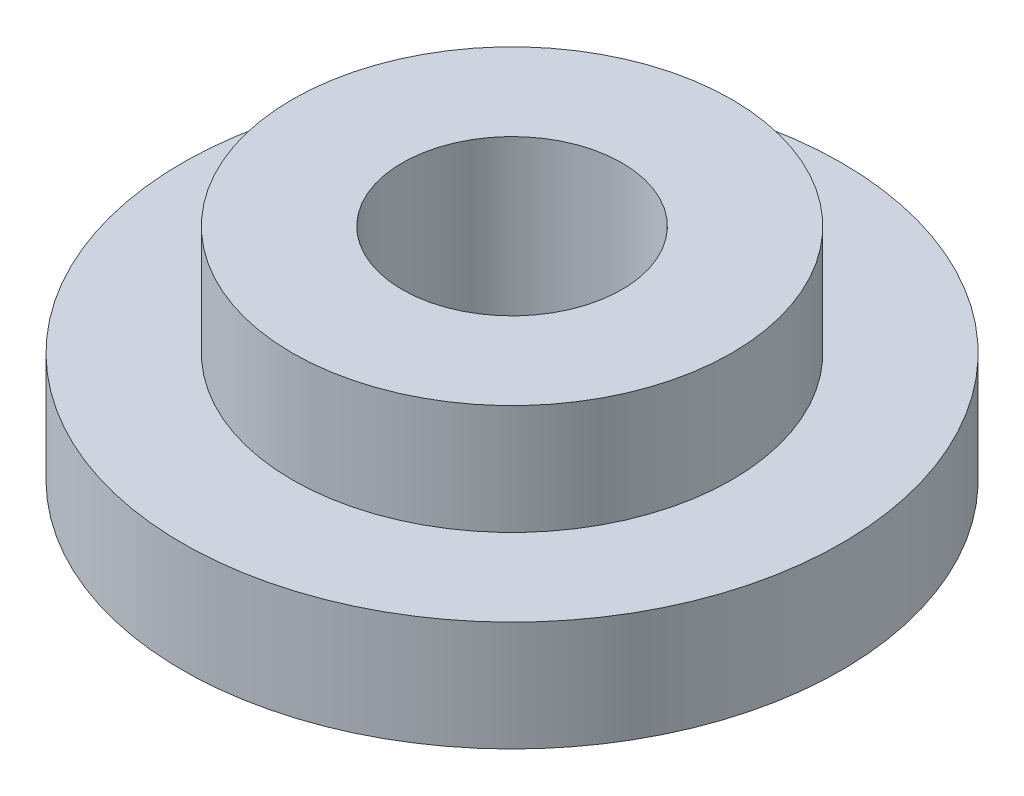
SolidWorks part; units mm, degrees
material "acero"
ref_plane "Alzado" through (0, 0, 0) normal (0, 0, 1) x (1, 0, 0)
ref_plane "Planta" through (0, 0, 0) normal (0, 1, 0) x (1, 0, 0)
ref_plane "Vista lateral" through (0, 0, 0) normal (1, 0, 0) x (0, 0, -1)
sketch "Croquis1" plane through (0, 0, 0) normal (0, 0, 1) x (1, 0, 0)
  line L0 (0, 0) -> (0, 4) construction
  line L1 (-2, 4) -> (-2, 0)
  line L2 (-2, 0) -> (-6, 0)
  line L3 (-6, 0) -> (-6, 2)
  line L4 (-6, 2) -> (-4, 2)
  line L5 (-4, 2) -> (-4, 4)
  line L6 (-4, 4) -> (-2, 4)
  dimension "D1" = 4
  dimension "D2" = 8
  dimension "D3" = 4
  dimension "D4" = 2
  dimension "D5" = 12
revolve "Revolución1" add sketch "Croquis1" angle 360 about L0
